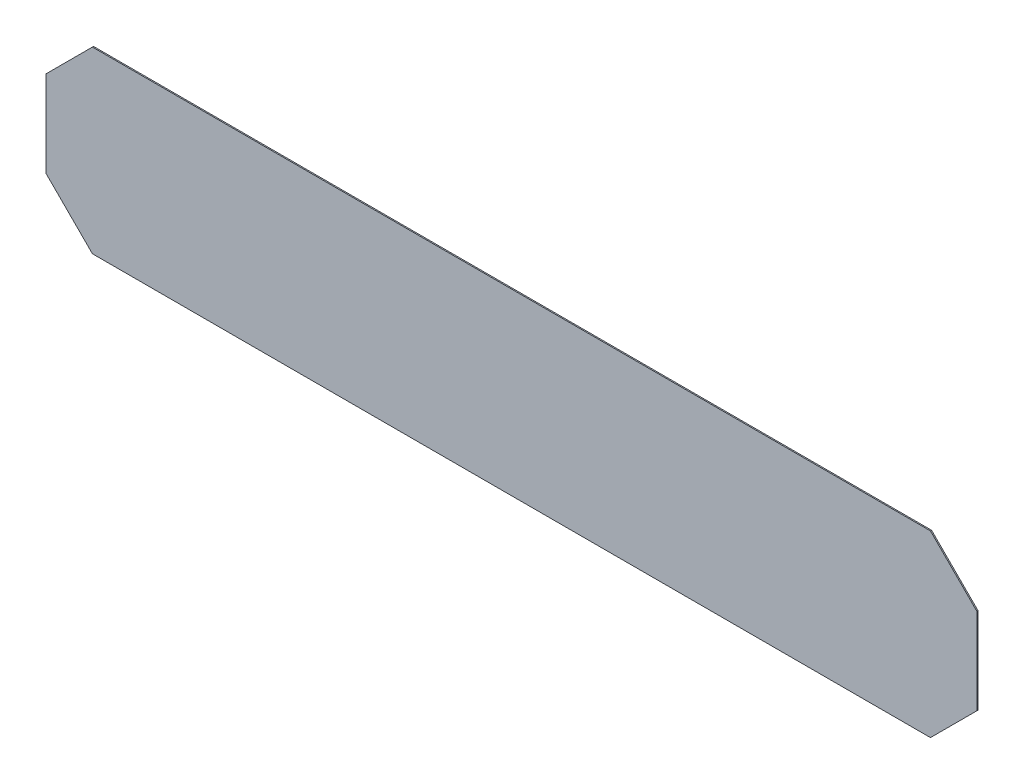
SolidWorks part; units mm, degrees
ref_plane "Front Plane" through (0, 0, 0) normal (0, 0, 1) x (1, 0, 0)
ref_plane "Top Plane" through (0, 0, 0) normal (0, 1, 0) x (1, 0, 0)
ref_plane "Right Plane" through (0, 0, 0) normal (1, 0, 0) x (0, 0, -1)
sketch "Sketch1" plane through (0, 0, 0) normal (0, 0, 1) x (1, 0, 0)
  line L1 (-41.275, 7.9375) -> (41.275, 7.9375)
  line L2 (-41.275, 7.9375) -> (-41.275, -7.9375)
  line L3 (-41.275, -7.9375) -> (41.275, -7.9375)
  line L4 (41.275, 7.9375) -> (41.275, -7.9375)
  line L5 (-41.275, 7.9375) -> (41.275, -7.9375) construction
  line L6 (-41.275, -7.9375) -> (41.275, 7.9375) construction
  point P0 (0, 0)
  dimension "D1" = 15.875
  dimension "D2" = 82.55
extrude "Boss-Extrude1" add sketch "Sketch1" along normal blind 0.1016
chamfer "Chamfer1" distance 4.1148 4 edges at (-41.275, 7.9375, 0.0508) (-41.275, -7.9375, 0.0508) (41.275, -7.9375, 0.0508) (41.275, 7.9375, 0.0508)
ref_plane "Plane1" through (0, 0, 0) normal (0, 1, 0) x (1, 0, 0)
ref_plane "Plane2" through (0, 0, 0) normal (1, 0, 0) x (0, 0, -1)
